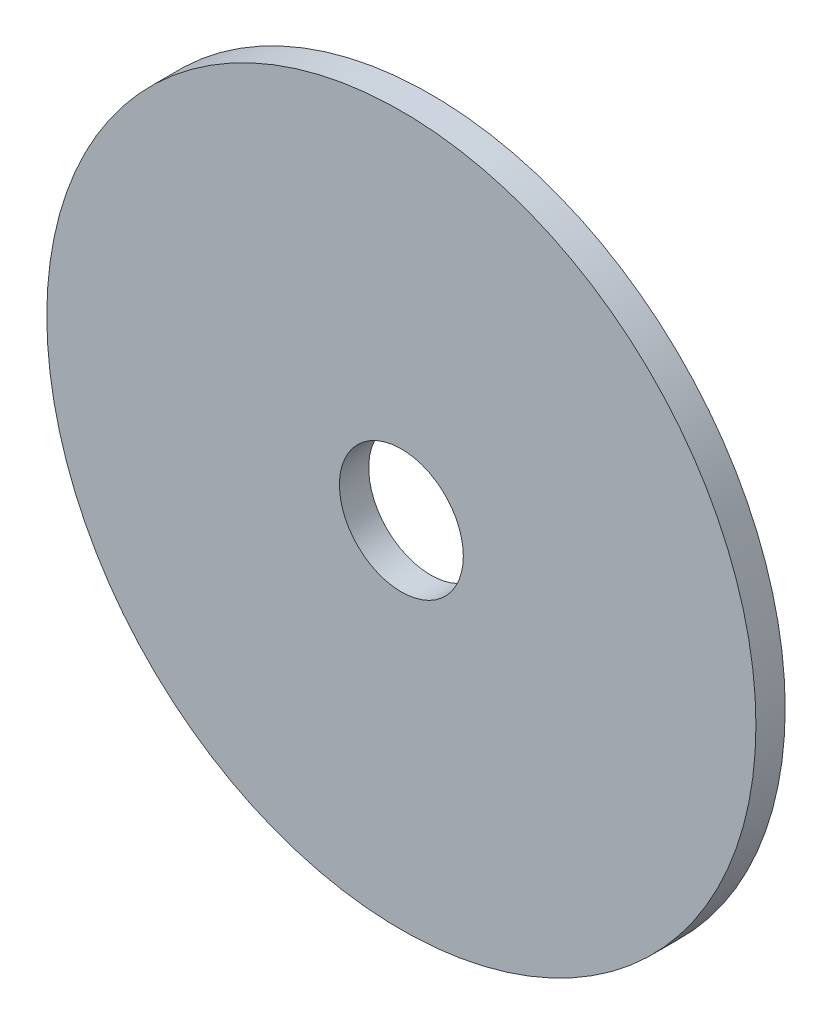
SolidWorks part; units mm, degrees
ref_plane "Front Plane" through (0, 0, 0) normal (0, 0, 1) x (1, 0, 0)
ref_plane "Top Plane" through (0, 0, 0) normal (0, 1, 0) x (1, 0, 0)
ref_plane "Right Plane" through (0, 0, 0) normal (1, 0, 0) x (0, 0, -1)
sketch "Sketch1" plane through (0, 0, 0) normal (0, 0, 1) x (1, 0, 0)
  circle A0 centre (-5.0652, 3.5095) radius 18.175
  circle A1 centre (-5.0652, 3.5095) radius 3.175
  point P4 (0, 0)
  dimension "D1" = 36.35
  dimension "D2" = 6.35
extrude "Boss-Extrude1" add sketch "Sketch1" along normal blind 1.5
